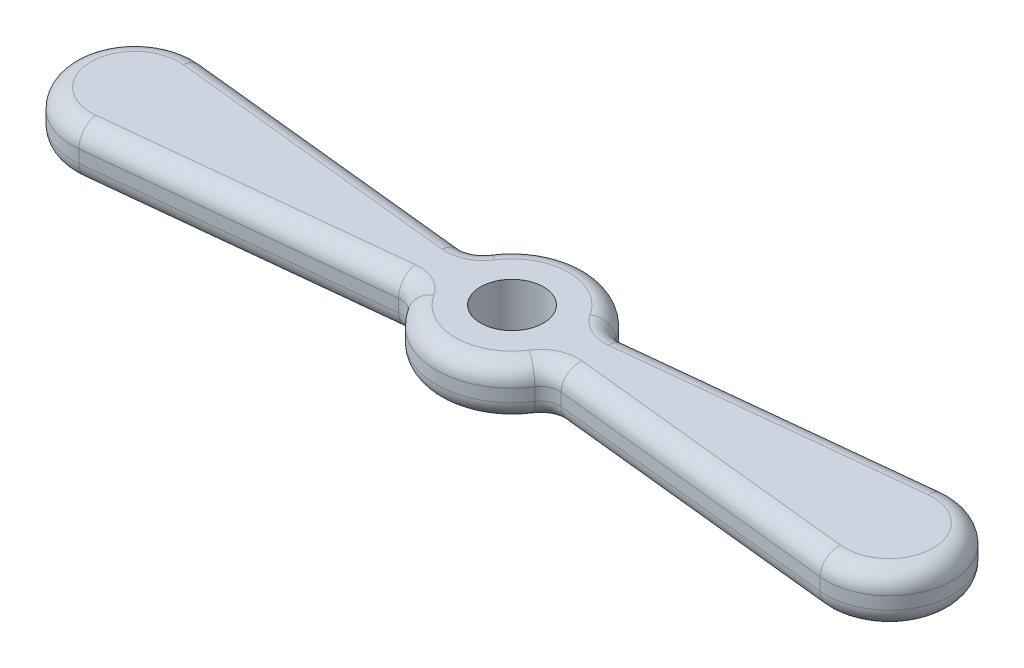
SolidWorks part; units mm, degrees
ref_plane "Front Plane" through (0, 0, 0) normal (0, 0, 1) x (1, 0, 0)
ref_plane "Top Plane" through (0, 0, 0) normal (0, 1, 0) x (1, 0, 0)
ref_plane "Right Plane" through (0, 0, 0) normal (1, 0, 0) x (0, 0, -1)
sketch "Sketch1" plane through (0, 0, 0) normal (0, 1, 0) x (1, 0, 0)
  line L0 (-60, 0) -> (0, 0) construction
  line L1 (-58.9547, 9.9452) -> (-10.9539, 4.9001)
  line L2 (-58.9547, -9.9452) -> (-10.9539, -4.9001)
  line L3 (0, 0) -> (0, 19.9033) construction
  line L4 (58.9547, -9.9452) -> (10.9539, -4.9001)
  line L5 (58.9547, 9.9452) -> (10.9539, 4.9001)
  circle A0 centre (0, 0) radius 5
  arc A1 (-10.9539, -4.9001) -> (10.9539, -4.9001) centre (0, 0) ccw
  arc A3 (-58.9547, 9.9452) -> (-58.9547, -9.9452) centre (-60, 0) ccw
  arc A5 (58.9547, 9.9452) -> (58.9547, -9.9452) centre (60, 0) cw
  arc A6 (10.9539, 4.9001) -> (-10.9539, 4.9001) centre (0, 0) ccw
  point P3 (0, 0)
  point P10 (0, 0)
  dimension "D1" = 24
  dimension "D2" = 20
  dimension "D4" = 10
  dimension "D3" = 60
  dimension "D5" = 6
extrude "Boss-Extrude2" add sketch "Sketch1" along normal blind 8
fillet "Fillet1" radius 3 4 edges at (-10.9539, 4, -4.9001) (-10.9539, 4, 4.9001) (10.9539, 4, -4.9001) (10.9539, 4, 4.9001)
fillet "Fillet2" radius 3 24 edges at (-70, 0, 0) (-35.949, 0, -7.5272) (-11.3298, 0, -5.389) (0, 0, -12) (11.3298, 0, -5.389) (35.949, 0, -7.5272) (70, 0, 0) (35.949, 0, 7.5272) (11.3298, 0, 5.389) (0, 0, 12) (-11.3298, 0, 5.389) (-70, 8, 0) (-35.949, 8, -7.5272) (-11.3298, 8, -5.389) (0, 8, -12) (11.3298, 8, -5.389) (35.949, 8, -7.5272) (70, 8, 0) (35.949, 8, 7.5272) (11.3298, 8, 5.389) (0, 8, 12) (-11.3298, 8, 5.389) (-35.949, 0, 7.5272) (-35.949, 8, 7.5272)
